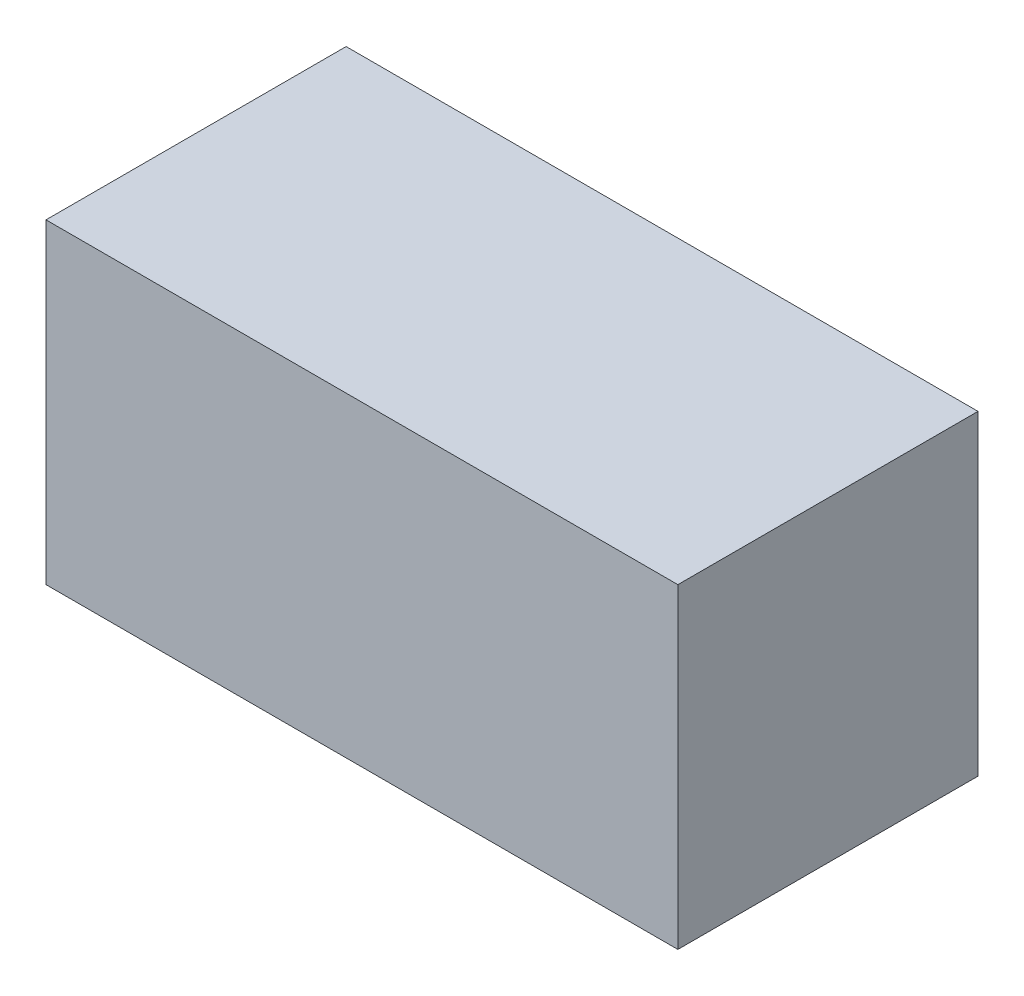
SolidWorks part; units mm, degrees
ref_plane "Front Plane" through (0, 0, 0) normal (0, 0, 1) x (1, 0, 0)
ref_plane "Top Plane" through (0, 0, 0) normal (0, 1, 0) x (1, 0, 0)
ref_plane "Right Plane" through (0, 0, 0) normal (1, 0, 0) x (0, 0, -1)
sketch "Sketch1" plane through (0, 0, 0) normal (0, 0, 1) x (1, 0, 0)
  line L1 (0, 0) -> (40, 0)
  line L2 (0, 0) -> (0, 20)
  line L3 (0, 20) -> (40, 20)
  line L4 (40, 0) -> (40, 20)
extrude "Boss-Extrude1" add sketch "Sketch1" against normal blind 19
